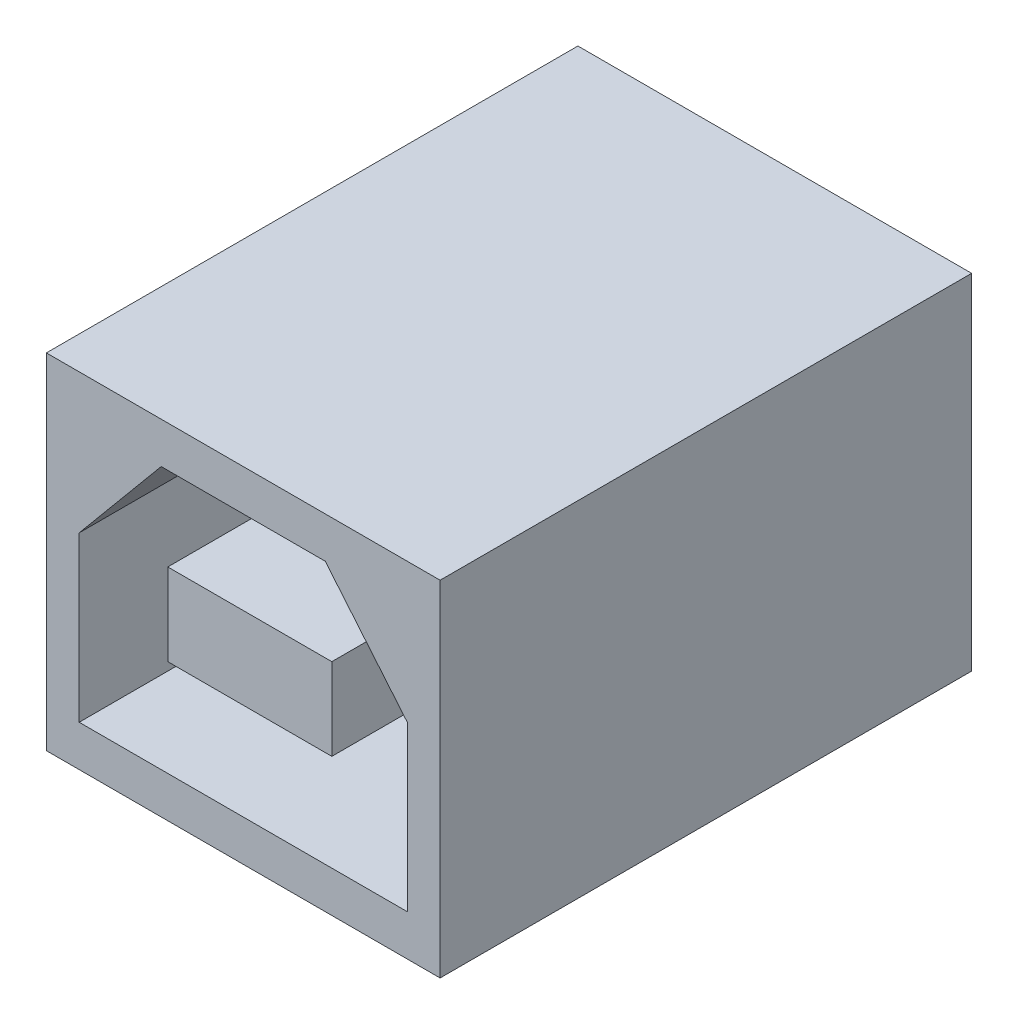
SolidWorks part; units mm, degrees
material "1.4000 (X6Cr13)"
ref_plane "Plan de face" through (0, 0, 0) normal (0, 0, 1) x (1, 0, 0)
ref_plane "Plan de dessus" through (0, 0, 0) normal (0, 1, 0) x (1, 0, 0)
ref_plane "Plan de droite" through (0, 0, 0) normal (1, 0, 0) x (0, 0, -1)
sketch "Esquisse1" plane through (0, 0, 0) normal (0, 0, 1) x (1, 0, 0)
  line L1 (-6, -5.25) -> (6, -5.25)
  line L2 (-6, -5.25) -> (-6, 5.25)
  line L3 (-6, 5.25) -> (6, 5.25)
  line L4 (6, -5.25) -> (6, 5.25)
  line L5 (-6, -5.25) -> (6, 5.25) construction
  line L6 (-6, 5.25) -> (6, -5.25) construction
  point P0 (0, 0)
  dimension "D1" = 12
  dimension "D2" = 10.5
extrude "Boss.-Extru.1" add sketch "Esquisse1" against normal blind 16.2
sketch "Esquisse2" plane through (0, 0, 0) normal (0, 0, 1) x (1, 0, 0)
  line L0 (-5, 1) -> (-2.5, 4)
  line L1 (-5, -4) -> (5, -4)
  line L2 (-5, -4) -> (-5, 1)
  line L3 (-2.5, 4) -> (2.5, 4)
  line L4 (5, -4) -> (5, 1)
  line L5 (-5, -4) -> (5, 4) construction
  line L6 (-5, 4) -> (5, -4) construction
  line L7 (0, 0) -> (0, 2.0876) construction
  line L8 (5, 1) -> (2.5, 4)
  point P0 (0, 0)
  dimension "D1" = 8
  dimension "D2" = 10
  dimension "D3" = 5
  dimension "D4" = 2.5
extrude "Enlèv. mat.-Extru.1" cut sketch "Esquisse2" against normal blind 14
sketch "Esquisse3" plane through (0, 0, -16.2) normal (0, 0, -1) x (-1, 0, 0)
  line L1 (-2.5, -1.25) -> (2.5, -1.25)
  line L2 (-2.5, -1.25) -> (-2.5, 1.25)
  line L3 (-2.5, 1.25) -> (2.5, 1.25)
  line L4 (2.5, -1.25) -> (2.5, 1.25)
  line L5 (-2.5, -1.25) -> (2.5, 1.25) construction
  line L6 (-2.5, 1.25) -> (2.5, -1.25) construction
  point P0 (0, 0)
  dimension "D1" = 5
  dimension "D2" = 2.5
extrude "Boss.-Extru.2" add sketch "Esquisse3" against normal blind 16
